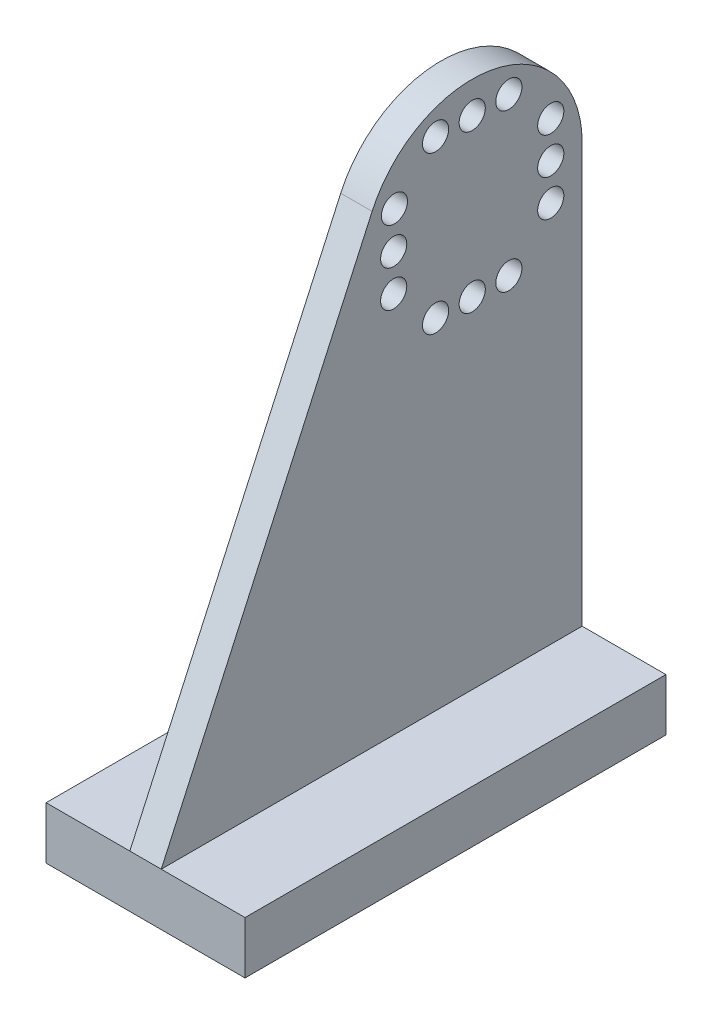
SolidWorks part; units mm, degrees
ref_plane "Front Plane" through (0, 0, 0) normal (0, 0, 1) x (1, 0, 0)
ref_plane "Top Plane" through (0, 0, 0) normal (0, 1, 0) x (1, 0, 0)
ref_plane "Right Plane" through (0, 0, 0) normal (1, 0, 0) x (0, 0, -1)
sketch "Sketch1" plane through (0, 0, 0) normal (1, 0, 0) x (0, 0, -1)
  line L4 (0, 0) -> (0, -7.5) construction
  line L5 (0, -7.5) -> (0, 0) construction
  line L12 (0, 0) -> (0, -7.5) construction
  line L17 (10.5, 0) -> (10.5, -40) construction
  line L18 (10.5, -40) -> (-29.7, -40) construction
  line L19 (-29.7, -40) -> (-9.5601, 4.3421) construction
  line L20 (10.5, 0) -> (10.5, -40)
  line L21 (10.5, -40) -> (-29.7, -40)
  line L22 (-29.7, -40) -> (-9.5601, 4.3421)
  line L23 (0, -7.5) -> (0, 0) construction
  circle A0 centre (0, 0) radius 10.5
  circle A1 centre (-3.5, 7.5) radius 1.25
  circle A2 centre (3.5, 7.5) radius 1.25
  circle A3 centre (7.5, 3.5) radius 1.25
  circle A4 centre (7.5, -3.5) radius 1.25
  circle A5 centre (3.5, -7.5) radius 1.25
  circle A6 centre (-3.5, -7.5) radius 1.25
  circle A7 centre (-7.5, -3.5) radius 1.25
  circle A8 centre (-7.4283, 3.4993) radius 1.25
  circle A9 centre (-7.5, 0) radius 1.25
  circle A10 centre (7.5, 0) radius 1.25
  circle A11 centre (0, -7.5) radius 1.25
  circle A12 centre (0, 7.5) radius 1.25
extrude "Boss-Extrude1" add sketch "Sketch1" along normal blind 3
sketch "Sketch2" plane through (0, -40, 0) normal (0, -1, 0) x (-1, 0, 0)
  line L1 (-3, 10.5) -> (0, 10.5)
  line L2 (-3, 10.5) -> (-3, -29.7)
  line L3 (-3, -29.7) -> (0, -29.7)
  line L4 (0, 10.5) -> (0, -29.7)
extrude "Boss-Extrude2" add sketch "Sketch2" along normal blind 5
sketch "Sketch4" plane through (0, 0, 0) normal (-1, 0, 0) x (0, 0, 1)
  line L0 (29.7, -40) -> (-10.5, -40) construction
  line L1 (-10.5, 0) -> (-10.5, -45) construction
  line L2 (-10.5, -40) -> (-10.5, -45) construction
  line L3 (-10.5, -45) -> (29.7, -45) construction
  line L4 (29.7, -45) -> (29.7, -40) construction
  line L6 (-10.5, -40) -> (29.7, -40)
  line L7 (-10.5, -40) -> (-10.5, -45)
  line L8 (-10.5, -45) -> (29.7, -45)
  line L9 (29.7, -40) -> (29.7, -45)
extrude "Boss-Extrude3" add sketch "Sketch4" along normal blind 8
mirror "Mirror1" about plane through (3, 0, 0) normal (1, 0, 0) of bodies 118 120
delete or keep bodies "Body-Delete/Keep 1" type delete bodies bodies 118
sketch "Sketch7" plane through (3, 0, 0) normal (-1, 0, 0) x (0, 0, 1)
  line L1 (-10.5, -45) -> (29.7, -45)
  line L2 (-10.5, -45) -> (-10.5, -40)
  line L3 (-10.5, -40) -> (29.7, -40)
  line L4 (29.7, -45) -> (29.7, -40)
extrude "Boss-Extrude4" add sketch "Sketch7" along normal blind 8
sketch "Sketch9" plane through (0, -40, 0) normal (0, 1, 0) x (1, 0, 0)
  line L0 (-1, 10.5) -> (-1, -29.7) construction
  line L1 (-5, 10.5) -> (3, 10.5) construction
  line L2 (-5, -29.7) -> (3, -29.7) construction
  line L3 (-1, -29.7) -> (-1, -19.7) construction
  line L4 (-1, 10.5) -> (-1, 0.5) construction
  circle A0 centre (-1, 0.5) radius 1.25
  circle A1 centre (-1, -19.7) radius 1.25
extrude "Cut-Extrude1" cut sketch "Sketch9" against normal blind 8
